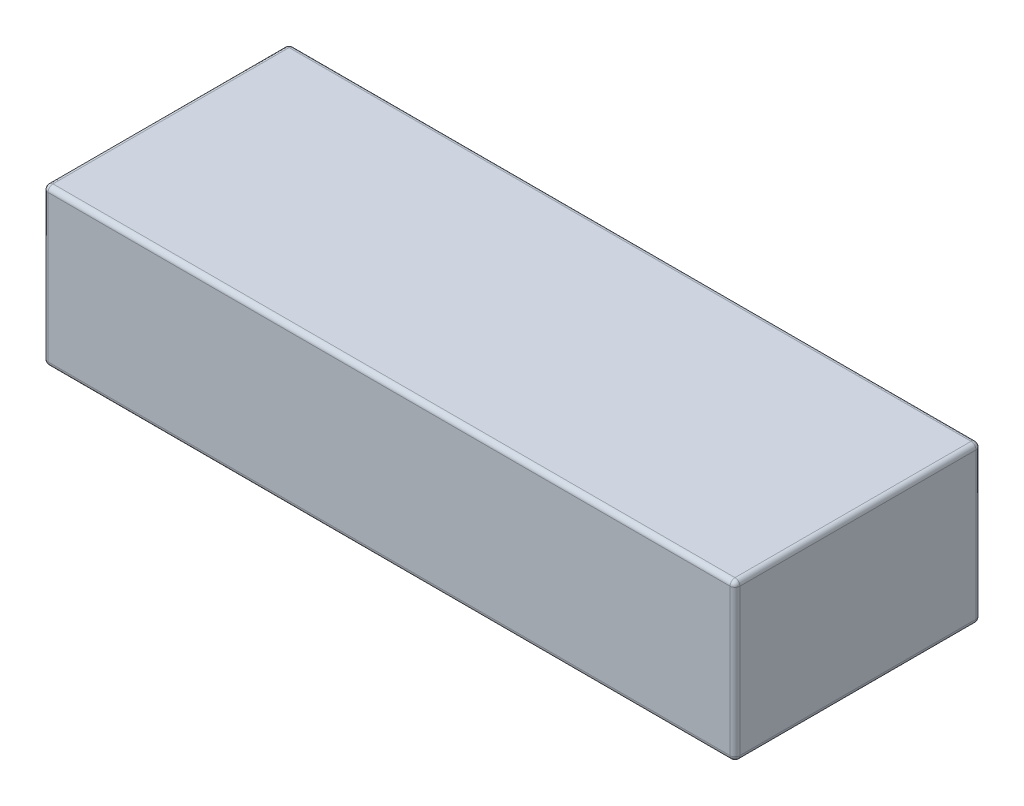
SolidWorks part; units mm, degrees
ref_plane "정면" through (0, 0, 0) normal (0, 0, 1) x (1, 0, 0)
ref_plane "윗면" through (0, 0, 0) normal (0, 1, 0) x (1, 0, 0)
ref_plane "우측면" through (0, 0, 0) normal (1, 0, 0) x (0, 0, -1)
sketch "Sketch1" plane through (0, 0, 0) normal (0, 1, 0) x (1, 0, 0)
  line L1 (-70.05, 24.9) -> (70.05, 24.9)
  line L2 (-70.05, 24.9) -> (-70.05, -24.9)
  line L3 (-70.05, -24.9) -> (70.05, -24.9)
  line L4 (70.05, 24.9) -> (70.05, -24.9)
  line L5 (-70.05, 24.9) -> (70.05, -24.9) construction
  line L6 (-70.05, -24.9) -> (70.05, 24.9) construction
  point P0 (0, 0)
  dimension "D1" = 140.1
  dimension "D2" = 49.8
extrude "Boss-Extrude1" add sketch "Sketch1" along normal mid plane 31.7
fillet "Fillet1" radius 1 4 edges at (0, -15.85, -24.9) (0, -15.85, 24.9) (0, 15.85, -24.9) (0, 15.85, 24.9)
fillet "Fillet2" radius 1 16 edges at (-70.05, 15.5571, -24.6071) (-70.05, 0, -24.9) (-70.05, -15.5571, -24.6071) (-70.05, -15.5571, 24.6071) (-70.05, 0, 24.9) (-70.05, 15.5571, 24.6071) (70.05, 15.5571, 24.6071) (70.05, 0, 24.9) (70.05, -15.5571, 24.6071) (70.05, -15.5571, -24.6071) (70.05, 0, -24.9) (70.05, 15.5571, -24.6071) (-70.05, -15.85, 0) (-70.05, 15.85, 0) (70.05, -15.85, 0) (70.05, 15.85, 0)
